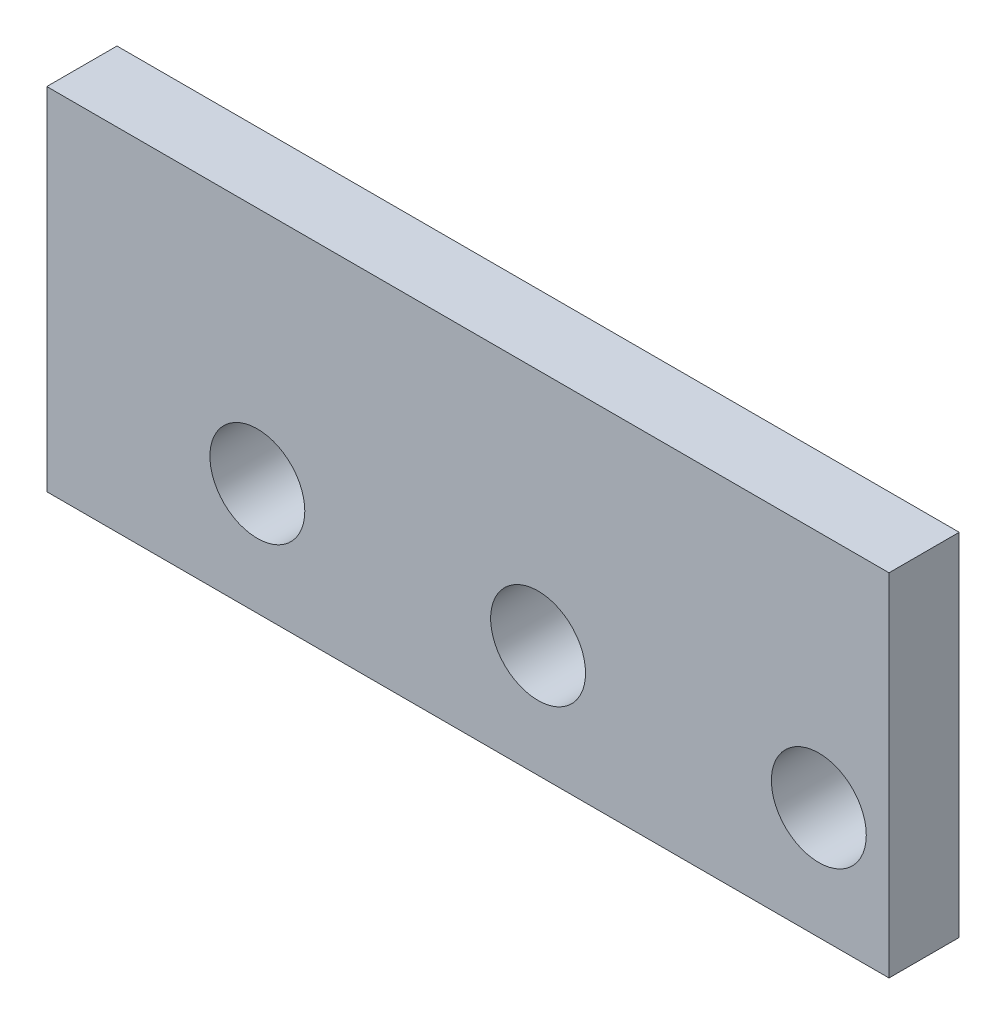
SolidWorks part; units mm, degrees
material "PET"
ref_plane "Front Plane" through (0, 0, 0) normal (0, 0, 1) x (1, 0, 0)
ref_plane "Top Plane" through (0, 0, 0) normal (0, 1, 0) x (1, 0, 0)
ref_plane "Right Plane" through (0, 0, 0) normal (1, 0, 0) x (0, 0, -1)
sketch "Sketch1" plane through (0, 0, 0) normal (0, 0, 1) x (1, 0, 0)
  line L0 (0, 5.08) -> (9.525, 5.08) construction
  line L1 (0, 0) -> (38.1, 0)
  line L2 (0, 0) -> (0, 15.875)
  line L3 (0, 15.875) -> (38.1, 15.875)
  line L4 (38.1, 0) -> (38.1, 15.875)
  line L5 (9.525, 5.08) -> (22.225, 5.08) construction
  line L6 (22.225, 5.08) -> (34.925, 5.08) construction
  line L7 (34.925, 5.08) -> (38.1, 5.08) construction
  circle A0 centre (9.525, 5.08) radius 2.1463
  circle A1 centre (22.225, 5.08) radius 2.1463
  circle A2 centre (34.925, 5.08) radius 2.1463
  point P12 (33.4194, 9.5295)
  point P14 (0, 0)
  point P15 (0, 0)
  point P16 (36.7549, 5.08)
  point P17 (0, 0)
  point P18 (0, 0)
  dimension "D4" = 4.2926
  dimension "D1" = 15.875
  dimension "D2" = 12.7
  dimension "D3" = 38.1
  dimension "D5" = 3.175
  dimension "D6" = 5.08
extrude "Boss-Extrude1" add sketch "Sketch1" along normal blind 3.175
